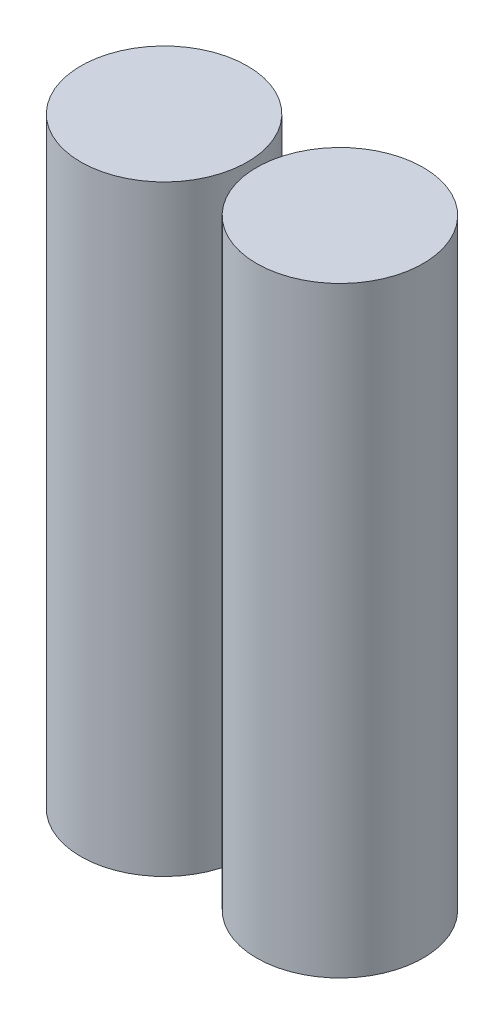
SolidWorks part; units mm, degrees
ref_plane "Front Plane" through (0, 0, 0) normal (0, 0, 1) x (1, 0, 0)
ref_plane "Top Plane" through (0, 0, 0) normal (0, 1, 0) x (1, 0, 0)
ref_plane "Right Plane" through (0, 0, 0) normal (1, 0, 0) x (0, 0, -1)
sketch "Sketch1" plane through (0, 0, 0) normal (0, 1, 0) x (1, 0, 0)
  line L0 (9, 0) -> (10, 0)
  circle A0 centre (0, 0) radius 9
  circle A1 centre (19, 0) radius 9
  dimension "D1" = 18
  dimension "D2" = 18
  dimension "D3" = 1
extrude "Boss-Extrude1" add sketch "Sketch1" along normal blind 65 contours A0 | A1
